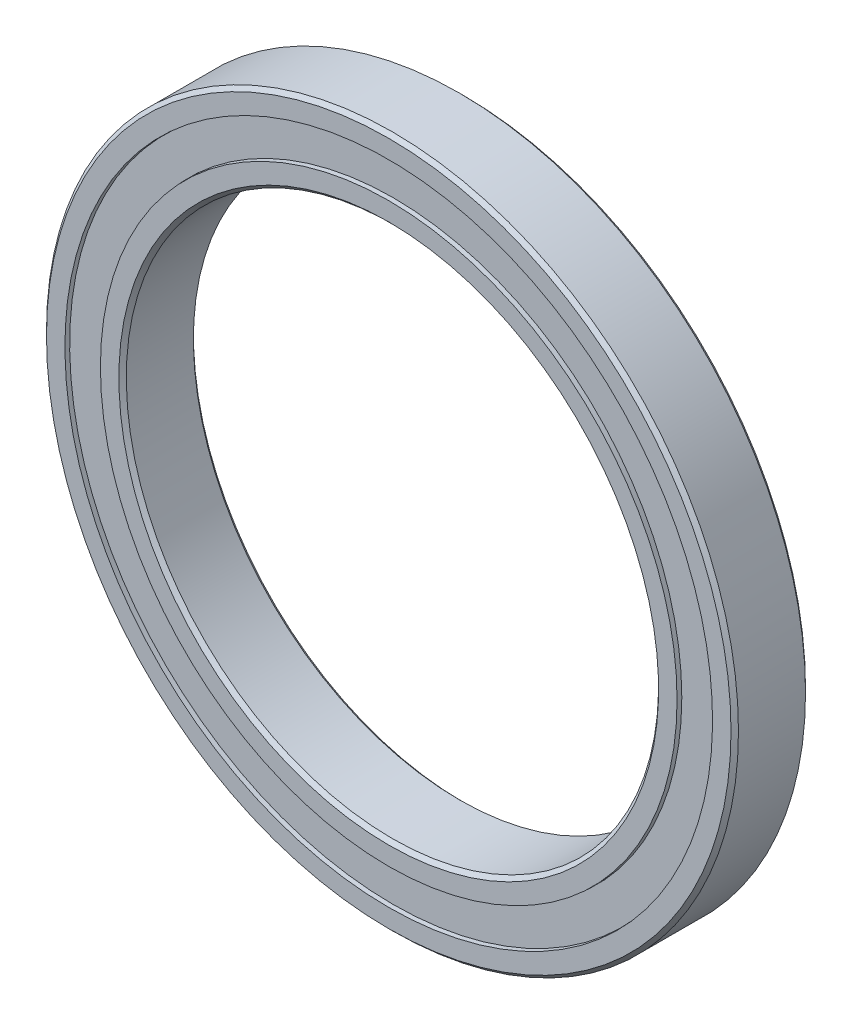
SolidWorks part; units mm, degrees
ref_plane "Front Plane" through (0, 0, 0) normal (0, 0, 1) x (1, 0, 0)
ref_plane "Top Plane" through (0, 0, 0) normal (0, 1, 0) x (1, 0, 0)
ref_plane "Right Plane" through (0, 0, 0) normal (1, 0, 0) x (0, 0, -1)
sketch "Sketch1" plane through (0, 0, 0) normal (0, 0, 1) x (1, 0, 0)
  circle A0 centre (0, 0) radius 32.5
  circle A1 centre (0, 0) radius 25
  dimension "OD" = 65
  dimension "ID" = 50
  dimension "For Shaft Diameter" = 50
  dimension "For Housing ID" = 65
sketch "Sketch8" plane through (0, 0, 0) normal (1, 0, 0) x (0, 0, -1)
  line L1 (-3.5, 32.5) -> (3.5, 32.5)
  line L2 (-3.5, 32.5) -> (-3.5, -32.5)
  line L3 (-3.5, -32.5) -> (3.5, -32.5)
  line L4 (3.5, 32.5) -> (3.5, -32.5)
  line L5 (-3.5, 32.5) -> (3.5, -32.5) construction
  line L6 (-3.5, -32.5) -> (3.5, 32.5) construction
  point P0 (0, 0)
  point P6 (0, -32.5)
  dimension "Width" = 7
sketch "Sketch5" plane through (0, 0, 0) normal (1, 0, 0) x (0, 0, -1)
  line L0 (-3.5, 0) -> (3.5, 0) construction
  line L1 (0, 32.5) -> (0, -32.5) construction
  line L2 (3.15, 32.5) -> (-3.15, 32.5)
  line L3 (-3.15, 32.5) -> (-3.5, 32.15)
  line L4 (-3.5, 32.15) -> (-3.5, 30.4167)
  line L5 (-3.5, 30.4167) -> (-1.5556, 30.4167)
  line L6 (3.5, 30.4167) -> (1.5556, 30.4167)
  line L7 (3.5, 32.15) -> (3.5, 30.4167)
  line L8 (3.15, 32.5) -> (3.5, 32.15)
  line L9 (0, 32.5) -> (0, 28.75) construction
  line L10 (0, 28.75) -> (0, 25) construction
  line L11 (-2.2798, 28.75) -> (-3.5, 28.75) construction
  line L12 (2.6994, 27.1087) -> (3.0804, 27.1087)
  line L13 (-2.6994, 27.1087) -> (-3.0804, 27.1087)
  line L14 (-2.6994, 27.1087) -> (-2.6994, 30.3913)
  line L15 (-2.6994, 30.3913) -> (-3.0804, 30.3913)
  line L16 (-3.0804, 27.1087) -> (-3.0804, 30.3913)
  line L17 (-2.6994, 27.1087) -> (-3.0804, 30.3913) construction
  line L18 (-2.6994, 30.3913) -> (-3.0804, 27.1087) construction
  line L19 (3.0804, 27.1087) -> (3.0804, 30.3913)
  line L20 (2.6994, 30.3913) -> (3.0804, 30.3913)
  line L21 (2.6994, 27.1087) -> (2.6994, 30.3913)
  line L22 (0, 32.5) -> (0, -32.5) construction
  line L23 (3.5, 0) -> (3.5, 32.5) construction
  line L24 (3.5, 32.5) -> (3.15, 32.5) construction
  line L25 (-3.5, 0) -> (-3.5, 32.5) construction
  line L26 (-3.5, 32.5) -> (-3.15, 32.5) construction
  line L27 (3.5, 0) -> (3.5, -32.5) construction
  line L28 (-3.5, 0) -> (-3.5, -32.5) construction
  line L29 (-3.5, -32.5) -> (3.5, -32.5) construction
  arc A0 (-1.5556, 30.4167) -> (1.5556, 30.4167) centre (0, 28.75) cw
  circle A1 centre (0, 28.75) radius 2.2798 construction
  point P14 (0, 25)
  point P15 (-2.8899, 28.75)
  dimension "D1" = 45
  dimension "D2" = 0.35
  dimension "D3" = 3.1111
  dimension "D4" = 1.6667
  dimension "D5" = 0.381
  dimension "D6" = 0.0254
revolve "Revolve1" add sketch "Sketch5" angle 360 about L0
sketch "Sketch3" plane through (0, 0, 0) normal (1, 0, 0) x (0, 0, -1)
  line L0 (-3.5, 27.0833) -> (-1.5556, 27.0833)
  line L1 (0, 32.5) -> (0, -32.5) construction
  line L2 (-3.5, 32.15) -> (-3.5, 30.4167) construction
  line L3 (-3.5, 27.0833) -> (-3.5, 25.35)
  line L4 (-3.15, 32.5) -> (-3.5, 32.15) construction
  line L5 (-3.5, 25.35) -> (-3.15, 25)
  line L6 (-3.15, 25) -> (3.15, 25)
  line L7 (3.15, 32.5) -> (3.15, -32.5) construction
  line L8 (3.15, 25) -> (3.5, 25.35)
  line L9 (3.5, -32.15) -> (3.5, 32.15) construction
  line L10 (3.5, 25.35) -> (3.5, 27.0833)
  line L11 (3.5, 27.0833) -> (1.5556, 27.0833)
  line L13 (3.15, 32.5) -> (3.5, 32.15) construction
  arc A0 (1.5556, 30.4167) -> (-1.5556, 30.4167) centre (0, 28.75) ccw construction
  arc A1 (1.5556, 27.0833) -> (-1.5556, 27.0833) centre (0, 28.75) cw
revolve "Revolve3" add sketch "Sketch3" angle 360 about L0
sketch "Sketch4" plane through (0, 0, 0) normal (1, 0, 0) x (0, 0, -1)
  line L0 (-2.2798, 28.75) -> (2.2798, 28.75)
  arc A2 (-2.2798, 28.75) -> (2.2798, 28.75) centre (0, 28.75) cw
  arc A3 (1.5556, 30.4167) -> (-1.5556, 30.4167) centre (0, 28.75) ccw construction
revolve "Revolve4" add sketch "Sketch4" angle 360 about L0
pattern_circular "CirPattern1" count 23 every 15.652 about axis through (0, 0, 0) along (0, 0, 1) of bodies 104
equation "\"D2@Sketch5\" = \"Width@Sketch8\" * .05"
equation "\"D3@Sketch5\" = \"Width@Sketch8\" / 2.25"
equation "\"D4@Sketch5\"=((\"OD@Sketch1\"-\"ID@Sketch1\")/2)/4.5"
equation "\"D2@CirPattern1\" = 360/\"Balls@CirPattern1\""
